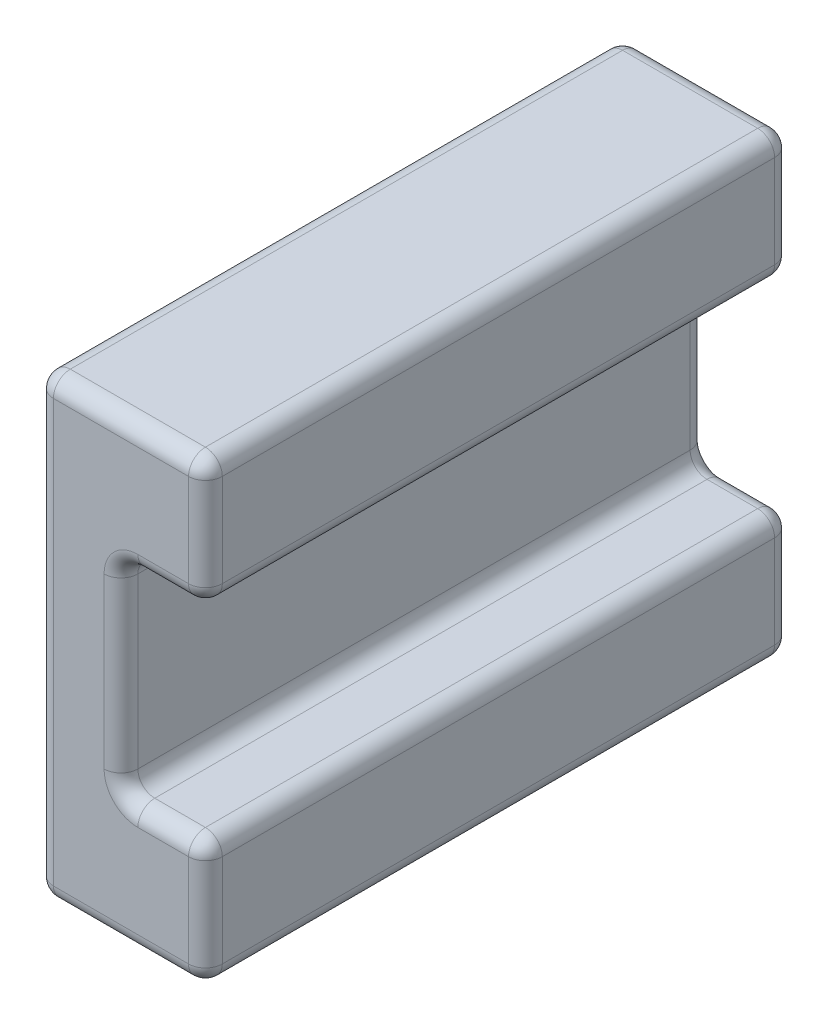
SolidWorks part; units mm, degrees
ref_plane "Front Plane" through (0, 0, 0) normal (0, 0, 1) x (1, 0, 0)
ref_plane "Top Plane" through (0, 0, 0) normal (0, 1, 0) x (1, 0, 0)
ref_plane "Right Plane" through (0, 0, 0) normal (1, 0, 0) x (0, 0, -1)
sketch "Sketch1" plane through (0, 0, 0) normal (0, 0, 1) x (1, 0, 0)
  line L0 (5, -6) -> (5, -13.5)
  line L1 (-5, 13.5) -> (5, 13.5)
  line L2 (-5, 13.5) -> (-5, -13.5)
  line L3 (-5, -13.5) -> (5, -13.5)
  line L4 (5, 13.5) -> (5, 6)
  line L5 (-5, 13.5) -> (5, -13.5) construction
  line L6 (-5, -13.5) -> (5, 13.5) construction
  line L7 (0, -6) -> (5, -6)
  line L8 (0, -6) -> (0, 6)
  line L9 (0, 6) -> (5, 6)
  line L11 (0, -6) -> (5, 0) construction
  line L12 (0, 6) -> (5, 0) construction
  point P0 (0, 0)
  point P6 (5, 0)
  dimension "D1" = 27
  dimension "D2" = 10
  dimension "D3" = 12
  dimension "D4" = 5
extrude "Boss-Extrude1" add sketch "Sketch1" along normal blind 34.7
sketch "Sketch3" plane through (-5, 0, 0) normal (-1, 0, 0) x (0, 0, 1)
  line L0 (0, 0) -> (5.5023, 0) construction
  line L1 (17.35, 15.8594) -> (17.35, 13.4331) construction
  circle A0 centre (9.85, 10) radius 1.7
  circle A1 centre (24.85, 10) radius 1.7
  circle A2 centre (24.85, -10) radius 1.7
  circle A3 centre (9.85, -10) radius 1.7
  dimension "D1" = 3.4
  dimension "D2" = 15
  dimension "D3" = 20
fillet "Fillet1" radius 1 24 edges at (-5, -13.5, 17.35) (2.5, -6, 0) (2.5, 6, 0) (-5, 0, 0) (0, -13.5, 0) (-5, 0, 34.7) (2.5, 6, 34.7) (2.5, -6, 34.7) (0, -13.5, 34.7) (0, -6, 17.35) (0, 0, 34.7) (0, 6, 17.35) (0, 0, 0) (5, -13.5, 17.35) (5, -9.75, 34.7) (5, -6, 17.35) (5, -9.75, 0) (5, 6, 17.35) (5, 9.75, 34.7) (5, 9.75, 0) (5, 13.5, 17.35) (0, 13.5, 34.7) (-5, 13.5, 17.35) (0, 13.5, 0)
hole_wizard "M3 Tapped Hole2" positions "3DSketch2" profile "Sketch5" tap size "M3" standard "ISO"
sketch3d "3DSketch2"
  point P0 (-5, 10, 9.85)
  point P3 (-5, 10, 24.85)
  point P6 (-5, -10, 24.85)
  point P9 (-5, -10, 9.85)
sketch "Sketch5" plane through (-5, 10, 9.85) normal (0, 1, 0) x (0, 0, 1)
  line L0 (0, 0) -> (0, 5)
  line L1 (0, 5) -> (1.25, 4.2489)
  line L2 (1.25, 4.2489) -> (1.25, 0.275)
  line L3 (1.25, 0.275) -> (1.525, 0)
  line L5 (1.525, 0) -> (0, 0)
  line L6 (-1.25, 0.275) -> (-1.525, 0) construction
  line L10 (0, 5) -> (-1.25, 4.2489) construction
  line L11 (0, -6.35) -> (0, 107.95) construction
  dimension "Tap Drill Dia." = 2.5
  dimension "Tap Drill Depth" = 5
  dimension "Near C'Sink Dia." = 3.05
  dimension "Near C'Sink Angle" = 90
  dimension "Drill Angle" = 118
cosmetic thread "Hole Thread5" parameters "D1"=6, "D2"=3
cosmetic thread "Hole Thread6" parameters "D1"=6, "D2"=3
cosmetic thread "Hole Thread7" parameters "D1"=6, "D2"=3
cosmetic thread "Hole Thread8" parameters "D1"=6, "D2"=3
